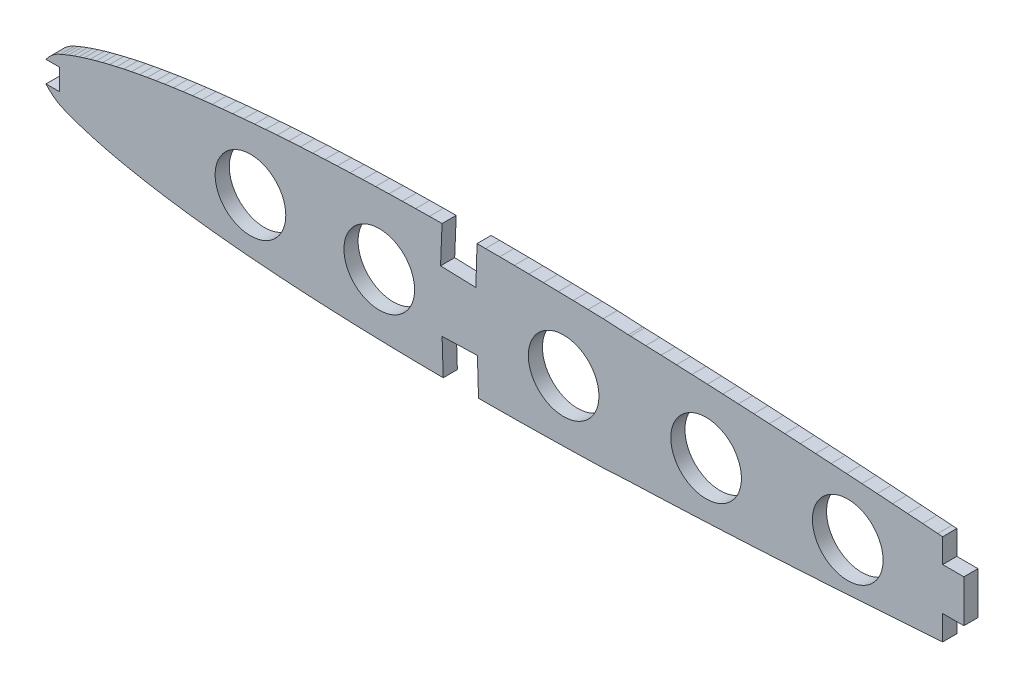
SolidWorks part; units mm, degrees
ref_plane "前视基准面" through (0, 0, 0) normal (0, 0, 1) x (1, 0, 0)
ref_plane "上视基准面" through (0, 0, 0) normal (0, 1, 0) x (1, 0, 0)
ref_plane "右视基准面" through (0, 0, 0) normal (1, 0, 0) x (0, 0, -1)
sketch "Model" plane through (0, 0, 0) normal (0, 0, 1) x (1, 0, 0)
  line L0 (15.1941, 17.7219) -> (17.1331, 17.7219)
  line L1 (17.1331, 17.7219) -> (17.1331, 14.7219)
  line L2 (17.1331, 14.7219) -> (15.1941, 14.7219)
  line L3 (76.1908, 25.6482) -> (76.0268, 20.1789)
  line L4 (76.0268, 20.1789) -> (71.0288, 20.3409)
  line L5 (71.0288, 20.3409) -> (71.2431, 25.6333)
  line L6 (76.4058, 6.7961) -> (76.2438, 11.9679)
  line L7 (76.2438, 11.9679) -> (71.2468, 11.8059)
  line L8 (71.2468, 11.8059) -> (71.4088, 6.8089)
  line L9 (142.0868, 22.6739) -> (141.3998, 22.7241)
  line L10 (141.3998, 22.7241) -> (139.2598, 22.8781)
  line L11 (139.2598, 22.8781) -> (137.1198, 23.0291)
  line L12 (137.1198, 23.0291) -> (134.9798, 23.1771)
  line L13 (134.9798, 23.1771) -> (132.8138, 23.3241)
  line L14 (132.8138, 23.3241) -> (130.6488, 23.4681)
  line L15 (130.6488, 23.4681) -> (128.4828, 23.6081)
  line L16 (128.4828, 23.6081) -> (126.2998, 23.7441)
  line L17 (126.2998, 23.7441) -> (124.1168, 23.8771)
  line L18 (124.1168, 23.8771) -> (121.9328, 24.0061)
  line L19 (121.9328, 24.0061) -> (119.7408, 24.1341)
  line L20 (119.7408, 24.1341) -> (117.5508, 24.2601)
  line L21 (117.5508, 24.2601) -> (115.3588, 24.3811)
  line L22 (115.3588, 24.3811) -> (113.1678, 24.4971)
  line L23 (113.1678, 24.4971) -> (110.9768, 24.6081)
  line L24 (110.9768, 24.6081) -> (108.7848, 24.7141)
  line L25 (108.7848, 24.7141) -> (106.6018, 24.8141)
  line L26 (106.6018, 24.8141) -> (104.4188, 24.9101)
  line L27 (104.4188, 24.9101) -> (102.2348, 25.0011)
  line L28 (102.2348, 25.0011) -> (100.0688, 25.0861)
  line L29 (100.0688, 25.0861) -> (97.9038, 25.1671)
  line L30 (97.9038, 25.1671) -> (97.6015, 25.1776)
  line L31 (97.6015, 25.1776) -> (94.0458, 25.3709)
  line L32 (94.0458, 25.3709) -> (91.9058, 25.4279)
  line L33 (91.9058, 25.4279) -> (89.7998, 25.4789)
  line L34 (89.7998, 25.4789) -> (87.6948, 25.5239)
  line L35 (87.6948, 25.5239) -> (85.5898, 25.5619)
  line L36 (85.5898, 25.5619) -> (83.5268, 25.5929)
  line L37 (83.5268, 25.5929) -> (81.4638, 25.6179)
  line L38 (81.4638, 25.6179) -> (79.4008, 25.6359)
  line L39 (79.4008, 25.6359) -> (77.3878, 25.6459)
  line L40 (77.3878, 25.6459) -> (76.1908, 25.6482)
  line L41 (71.2431, 25.6333) -> (69.4558, 25.6169)
  line L42 (69.4558, 25.6169) -> (67.5018, 25.5919)
  line L43 (67.5018, 25.5919) -> (65.6148, 25.5589)
  line L44 (65.6148, 25.5589) -> (63.7278, 25.5169)
  line L45 (63.7278, 25.5169) -> (61.8408, 25.4679)
  line L46 (61.8408, 25.4679) -> (60.0268, 25.4119)
  line L47 (60.0268, 25.4119) -> (58.2138, 25.3479)
  line L48 (58.2138, 25.3479) -> (56.4008, 25.2749)
  line L49 (56.4008, 25.2749) -> (54.6668, 25.1969)
  line L50 (54.6668, 25.1969) -> (52.9348, 25.1099)
  line L51 (52.9348, 25.1099) -> (51.2028, 25.0139)
  line L52 (51.2028, 25.0139) -> (49.5568, 24.9119)
  line L53 (49.5568, 24.9119) -> (47.9128, 24.8019)
  line L54 (47.9128, 24.8019) -> (46.2688, 24.6809)
  line L55 (46.2688, 24.6809) -> (44.7168, 24.5569)
  line L56 (44.7168, 24.5569) -> (43.1668, 24.4229)
  line L57 (43.1668, 24.4229) -> (41.6178, 24.2779)
  line L58 (41.6178, 24.2779) -> (40.1658, 24.1329)
  line L59 (40.1658, 24.1329) -> (38.7148, 23.9779)
  line L60 (38.7148, 23.9779) -> (37.2658, 23.8109)
  line L61 (37.2658, 23.8109) -> (35.9198, 23.6459)
  line L62 (35.9198, 23.6459) -> (34.5768, 23.4689)
  line L63 (34.5768, 23.4689) -> (33.2348, 23.2799)
  line L64 (33.2348, 23.2799) -> (31.9998, 23.0939)
  line L65 (31.9998, 23.0939) -> (30.7678, 22.8969)
  line L66 (30.7678, 22.8969) -> (29.5378, 22.6869)
  line L67 (29.5378, 22.6869) -> (28.4188, 22.4839)
  line L68 (28.4188, 22.4839) -> (27.3028, 22.2689)
  line L69 (27.3028, 22.2689) -> (26.1898, 22.0399)
  line L70 (26.1898, 22.0399) -> (25.1908, 21.8209)
  line L71 (25.1908, 21.8209) -> (24.1958, 21.5889)
  line L72 (24.1958, 21.5889) -> (23.2028, 21.3419)
  line L73 (23.2028, 21.3419) -> (22.3278, 21.1119)
  line L74 (22.3278, 21.1119) -> (21.4568, 20.8679)
  line L75 (21.4568, 20.8679) -> (20.5898, 20.6069)
  line L76 (20.5898, 20.6069) -> (19.8408, 20.3669)
  line L77 (19.8408, 20.3669) -> (19.0978, 20.1109)
  line L78 (19.0978, 20.1109) -> (18.3618, 19.8369)
  line L79 (18.3618, 19.8369) -> (17.7438, 19.5889)
  line L80 (17.7438, 19.5889) -> (17.2225, 19.3657)
  line L81 (17.227, 13.0761) -> (17.7438, 12.8549)
  line L82 (17.7438, 12.8549) -> (18.3618, 12.6079)
  line L83 (18.3618, 12.6079) -> (19.0978, 12.3329)
  line L84 (19.0978, 12.3329) -> (19.8408, 12.0769)
  line L85 (19.8408, 12.0769) -> (20.5898, 11.8369)
  line L86 (20.5898, 11.8369) -> (21.4568, 11.5769)
  line L87 (21.4568, 11.5769) -> (22.3278, 11.3319)
  line L88 (22.3278, 11.3319) -> (23.2028, 11.1019)
  line L89 (23.2028, 11.1019) -> (24.1958, 10.8559)
  line L90 (24.1958, 10.8559) -> (25.1908, 10.6229)
  line L91 (25.1908, 10.6229) -> (26.1898, 10.4039)
  line L92 (26.1898, 10.4039) -> (27.3028, 10.1749)
  line L93 (27.3028, 10.1749) -> (28.4188, 9.9599)
  line L94 (28.4188, 9.9599) -> (29.5378, 9.7569)
  line L95 (29.5378, 9.7569) -> (30.7678, 9.5469)
  line L96 (30.7678, 9.5469) -> (31.9998, 9.3499)
  line L97 (31.9998, 9.3499) -> (33.2348, 9.1649)
  line L98 (33.2348, 9.1649) -> (34.5768, 8.9749)
  line L99 (34.5768, 8.9749) -> (35.9198, 8.7979)
  line L100 (35.9198, 8.7979) -> (37.2658, 8.6329)
  line L101 (37.2658, 8.6329) -> (38.7148, 8.4659)
  line L102 (38.7148, 8.4659) -> (40.1658, 8.3109)
  line L103 (40.1658, 8.3109) -> (41.6178, 8.1659)
  line L104 (41.6178, 8.1659) -> (43.1668, 8.0209)
  line L105 (43.1668, 8.0209) -> (44.7168, 7.8879)
  line L106 (44.7168, 7.8879) -> (46.2688, 7.7639)
  line L107 (46.2688, 7.7639) -> (47.9128, 7.6429)
  line L108 (47.9128, 7.6429) -> (49.5568, 7.5319)
  line L109 (49.5568, 7.5319) -> (51.2028, 7.4309)
  line L110 (51.2028, 7.4309) -> (52.9348, 7.3339)
  line L111 (52.9348, 7.3339) -> (54.6668, 7.2469)
  line L112 (54.6668, 7.2469) -> (56.4008, 7.1689)
  line L113 (56.4008, 7.1689) -> (58.2138, 7.0959)
  line L114 (58.2138, 7.0959) -> (60.0268, 7.0319)
  line L115 (60.0268, 7.0319) -> (61.8408, 6.9759)
  line L116 (61.8408, 6.9759) -> (63.7278, 6.9269)
  line L117 (63.7278, 6.9269) -> (65.6148, 6.8859)
  line L118 (65.6148, 6.8859) -> (67.5018, 6.8529)
  line L119 (67.5018, 6.8529) -> (69.4558, 6.8269)
  line L120 (69.4558, 6.8269) -> (71.4088, 6.8089)
  line L121 (76.4058, 6.7961) -> (77.3878, 6.7979)
  line L122 (77.3878, 6.7979) -> (79.4008, 6.8089)
  line L123 (79.4008, 6.8089) -> (81.4638, 6.8259)
  line L124 (81.4638, 6.8259) -> (83.5268, 6.8509)
  line L125 (83.5268, 6.8509) -> (85.5898, 6.8819)
  line L126 (85.5898, 6.8819) -> (87.6948, 6.9199)
  line L127 (87.6948, 6.9199) -> (89.7998, 6.9649)
  line L128 (89.7998, 6.9649) -> (91.9058, 7.0159)
  line L129 (91.9058, 7.0159) -> (94.0458, 7.0729)
  line L130 (94.0458, 7.0729) -> (97.602, 7.2707)
  line L131 (97.602, 7.2707) -> (97.9038, 7.2811)
  line L132 (97.9038, 7.2811) -> (100.0688, 7.3621)
  line L133 (100.0688, 7.3621) -> (102.2348, 7.4471)
  line L134 (102.2348, 7.4471) -> (104.4188, 7.5381)
  line L135 (104.4188, 7.5381) -> (106.6018, 7.6341)
  line L136 (106.6018, 7.6341) -> (108.7848, 7.7341)
  line L137 (108.7848, 7.7341) -> (110.9768, 7.8401)
  line L138 (110.9768, 7.8401) -> (113.1678, 7.9511)
  line L139 (113.1678, 7.9511) -> (115.3588, 8.0671)
  line L140 (115.3588, 8.0671) -> (117.5508, 8.1891)
  line L141 (117.5508, 8.1891) -> (119.7408, 8.3141)
  line L142 (119.7408, 8.3141) -> (121.9328, 8.4421)
  line L143 (121.9328, 8.4421) -> (124.1168, 8.5721)
  line L144 (124.1168, 8.5721) -> (126.2998, 8.7041)
  line L145 (126.2998, 8.7041) -> (128.4828, 8.8401)
  line L146 (128.4828, 8.8401) -> (130.6488, 8.9801)
  line L147 (130.6488, 8.9801) -> (132.8138, 9.1241)
  line L148 (132.8138, 9.1241) -> (134.9798, 9.2711)
  line L149 (134.9798, 9.2711) -> (137.1198, 9.4191)
  line L150 (137.1198, 9.4191) -> (139.2598, 9.5701)
  line L151 (139.2598, 9.5701) -> (141.3998, 9.7241)
  line L152 (141.3998, 9.7241) -> (142.0888, 9.7745)
  line L153 (142.0868, 22.6739) -> (142.0868, 19.2595)
  line L154 (142.0868, 19.2595) -> (145.0868, 19.2595)
  line L155 (145.0868, 19.2595) -> (145.0868, 13.2595)
  line L156 (145.0868, 13.2595) -> (142.0868, 13.2595)
  line L157 (142.0868, 13.2595) -> (142.0888, 9.7745)
  circle A0 centre (62.3548, 15.5716) radius 4.9992
  arc A1 (17.2225, 19.3657) -> (15.1941, 17.7219) centre (18.985, 15.1174) ccw
  arc A2 (15.1941, 14.7219) -> (17.227, 13.0761) centre (20.4599, 19.1479) ccw
  circle A3 centre (88.4446, 15.5716) radius 4.9992
  circle A4 centre (108.6103, 15.5716) radius 4.9992
  circle A5 centre (128.6514, 15.5716) radius 4.9992
  circle A6 centre (44.1298, 15.5716) radius 4.9992
  point P173 (0, 0)
  point P174 (76.2012, 25.6482)
extrude "凸台-拉伸1" add sketch "Model" along normal blind 2
